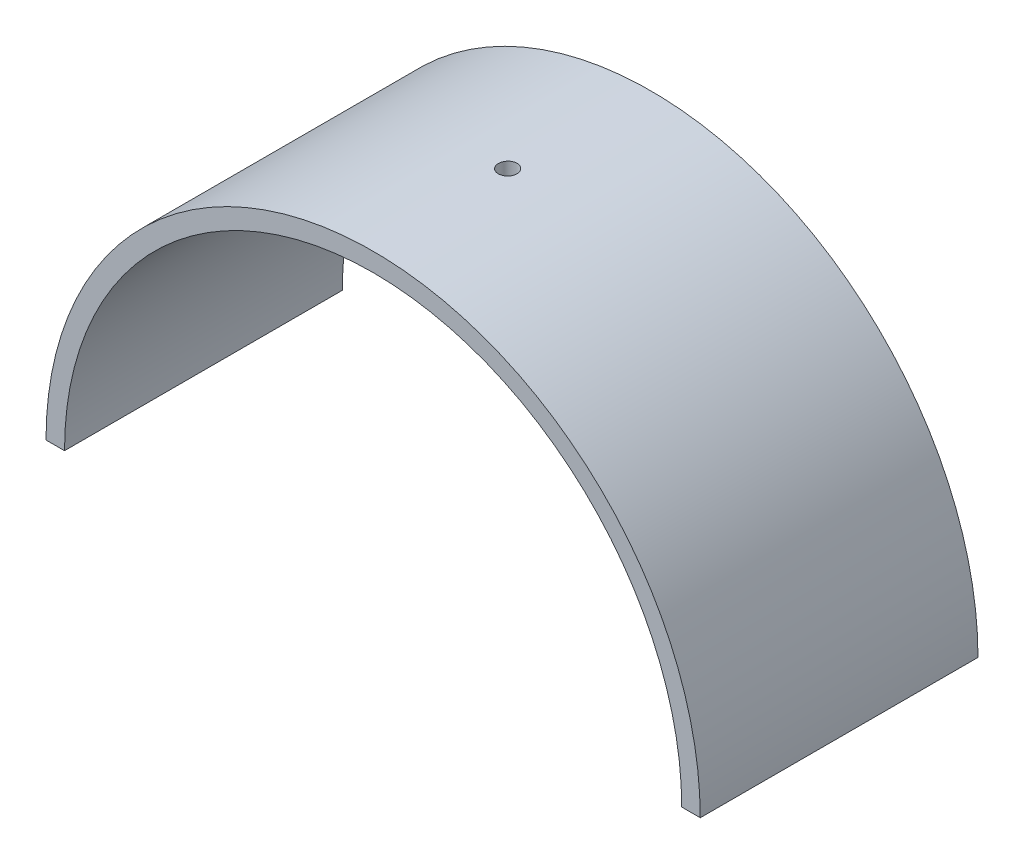
SolidWorks part; units mm, degrees
ref_plane "Front Plane" through (0, 0, 0) normal (0, 0, 1) x (1, 0, 0)
ref_plane "Top Plane" through (0, 0, 0) normal (0, 1, 0) x (1, 0, 0)
ref_plane "Right Plane" through (0, 0, 0) normal (1, 0, 0) x (0, 0, -1)
sketch "Sketch1" plane through (0, 0, 0) normal (0, 1, 0) x (1, 0, 0)
  line L0 (-51.5, 27.8343) -> (-51.5, -28.2642) construction
  line L1 (-1.5, 22.5) -> (1.5, 22.5)
  line L2 (-1.5, 22.5) -> (-1.5, -22.5)
  line L3 (-1.5, -22.5) -> (1.5, -22.5)
  line L4 (1.5, 22.5) -> (1.5, -22.5)
  line L5 (-1.5, 22.5) -> (1.5, -22.5) construction
  line L6 (-1.5, -22.5) -> (1.5, 22.5) construction
  point P0 (0, 0)
  dimension "D1" = 45
  dimension "D2" = 3
  dimension "D3" = 50
revolve "Revolve1" add sketch "Sketch1" angle 180 about L0
ref_plane "Plane1" through (0, 54, 0) normal (0, 1, 0) x (1, 0, 0)
sketch "Sketch2" plane through (0, 54, 0) normal (0, 1, 0) x (1, 0, 0)
  line L0 (-1.5, 22.5) -> (-101.5, 22.5) construction
  line L1 (1.5, -22.5) -> (1.5, 22.5) construction
  circle A0 centre (-52.2035, 0) radius 1.5
  dimension "D1" = 22.5
  dimension "D2" = 53.7035
extrude "Cut-Extrude1" cut sketch "Sketch2" against normal blind 10
